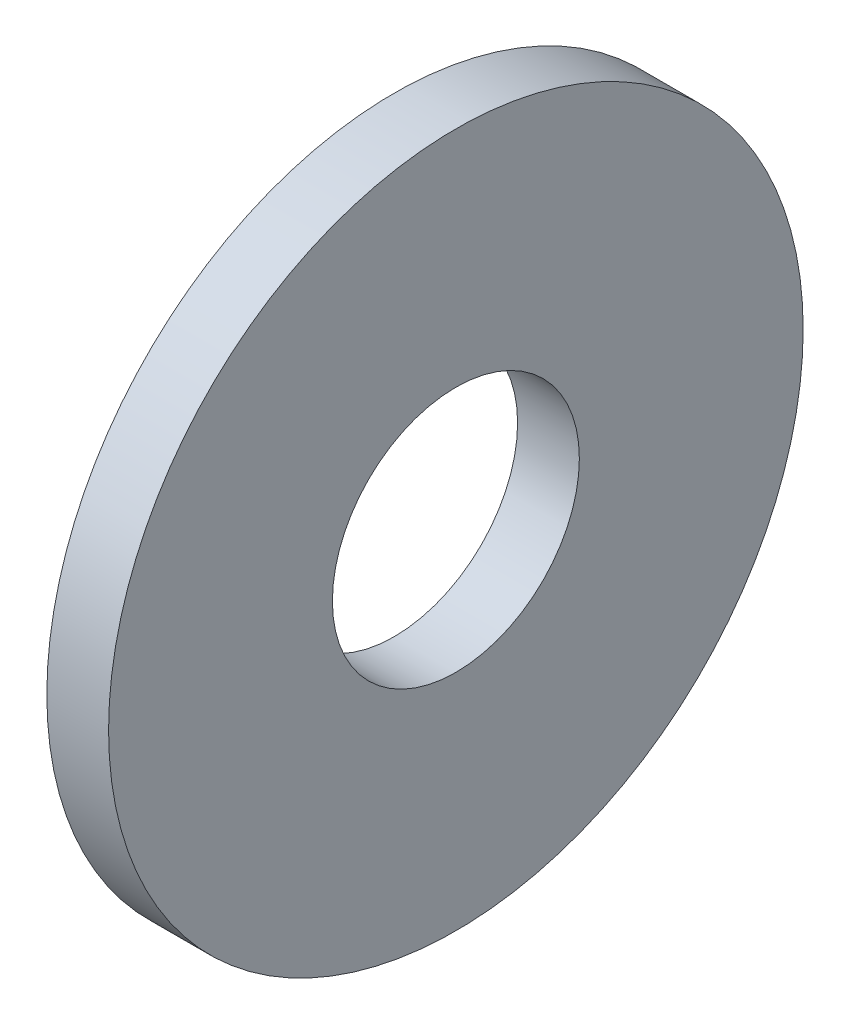
SolidWorks part; units mm, degrees
ref_plane "Plane1" through (0, 0, 0) normal (0, 0, 1) x (1, 0, 0)
ref_plane "Plane2" through (0, 0, 0) normal (0, 1, 0) x (1, 0, 0)
ref_plane "Plane3" through (0, 0, 0) normal (1, 0, 0) x (0, 0, -1)
sketch "Sketch1" plane through (0, 0, 0) normal (0, 0, 1) x (1, 0, 0)
  line L0 (-34.925, 0) -> (9.525, 0) construction
  line L1 (0, 3.2) -> (0, 9)
  line L2 (0, 9) -> (-1.6, 9)
  line L3 (-1.6, 9) -> (-1.6, 3.2)
  line L4 (-1.6, 3.2) -> (0, 3.2)
  dimension "Thickness" = 1.6
  dimension "Inside_dia" = 6.4
  dimension "Outside_dia" = 18
revolve "Base-Revolve" add sketch "Sketch1" angle 360 about L0
